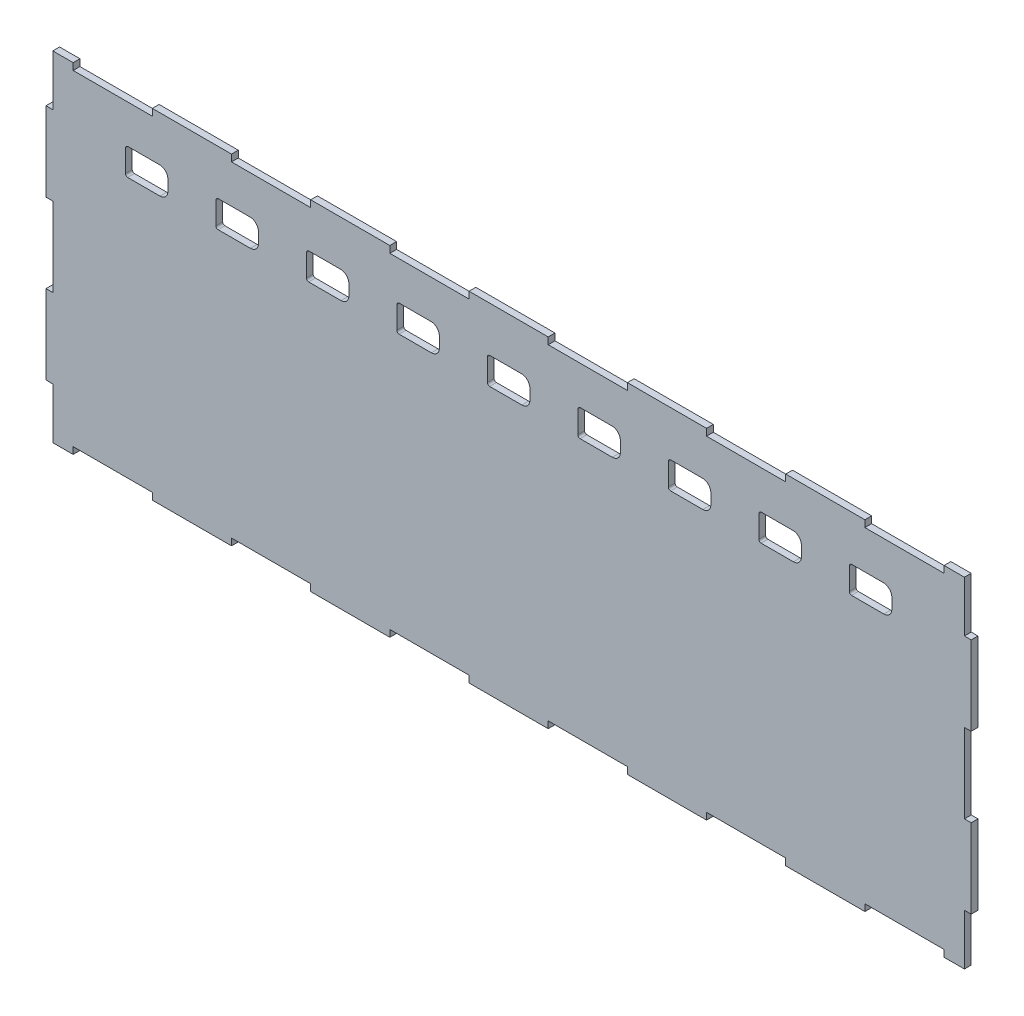
SolidWorks part; units mm, degrees
ref_plane "Front Plane" through (0, 0, 0) normal (0, 0, 1) x (1, 0, 0)
ref_plane "Top Plane" through (0, 0, 0) normal (0, 1, 0) x (1, 0, 0)
ref_plane "Right Plane" through (0, 0, 0) normal (1, 0, 0) x (0, 0, -1)
sketch "Model" plane through (0, 0, 0) normal (0, 0, 1) x (1, 0, 0)
  line L0 (201.5, 75) -> (192.5, 75)
  line L1 (192.5, 75) -> (192.5, 72)
  line L2 (192.5, 72) -> (157.5, 72)
  line L3 (157.5, 72) -> (157.5, 75)
  line L4 (157.5, 75) -> (122.5, 75)
  line L5 (122.5, 75) -> (122.5, 72)
  line L6 (122.5, 72) -> (87.5, 72)
  line L7 (87.5, 72) -> (87.5, 75)
  line L8 (87.5, 75) -> (52.5, 75)
  line L9 (52.5, 75) -> (52.5, 72)
  line L10 (52.5, 72) -> (17.5, 72)
  line L11 (17.5, 72) -> (17.5, 75)
  line L12 (17.5, 75) -> (-17.5, 75)
  line L13 (-17.5, 75) -> (-17.5, 72)
  line L14 (-17.5, 72) -> (-52.5, 72)
  line L15 (-52.5, 72) -> (-52.5, 75)
  line L16 (-52.5, 75) -> (-87.5, 75)
  line L17 (-87.5, 75) -> (-87.5, 72)
  line L18 (-87.5, 72) -> (-122.5, 72)
  line L19 (-122.5, 72) -> (-122.5, 75)
  line L20 (-122.5, 75) -> (-157.5, 75)
  line L21 (-157.5, 75) -> (-157.5, 72)
  line L22 (-157.5, 72) -> (-192.5, 72)
  line L23 (-192.5, 72) -> (-192.5, 75)
  line L24 (-192.5, 75) -> (-201.5, 75)
  line L25 (-201.5, 75) -> (-201.5, 72)
  line L26 (-201.5, 72) -> (-201.5, 52.5)
  line L27 (-201.5, 52.5) -> (-204.5, 52.5)
  line L28 (-204.5, 52.5) -> (-204.5, 17.5)
  line L29 (-204.5, 17.5) -> (-201.5, 17.5)
  line L30 (-201.5, 17.5) -> (-201.5, -17.5)
  line L31 (-201.5, -17.5) -> (-204.5, -17.5)
  line L32 (-204.5, -17.5) -> (-204.5, -52.5)
  line L33 (-204.5, -52.5) -> (-201.5, -52.5)
  line L34 (-201.5, -52.5) -> (-201.5, -72)
  line L35 (-201.5, -72) -> (-201.5, -75)
  line L36 (-201.5, -75) -> (-192.5, -75)
  line L37 (-192.5, -75) -> (-192.5, -72)
  line L38 (-192.5, -72) -> (-157.5, -72)
  line L39 (-157.5, -72) -> (-157.5, -75)
  line L40 (-157.5, -75) -> (-122.5, -75)
  line L41 (-122.5, -75) -> (-122.5, -72)
  line L42 (-122.5, -72) -> (-87.5, -72)
  line L43 (-87.5, -72) -> (-87.5, -75)
  line L44 (-87.5, -75) -> (-52.5, -75)
  line L45 (-52.5, -75) -> (-52.5, -72)
  line L46 (-52.5, -72) -> (-17.5, -72)
  line L47 (-17.5, -72) -> (-17.5, -75)
  line L48 (-17.5, -75) -> (17.5, -75)
  line L49 (17.5, -75) -> (17.5, -72)
  line L50 (17.5, -72) -> (52.5, -72)
  line L51 (52.5, -72) -> (52.5, -75)
  line L52 (52.5, -75) -> (87.5, -75)
  line L53 (87.5, -75) -> (87.5, -72)
  line L54 (87.5, -72) -> (122.5, -72)
  line L55 (122.5, -72) -> (122.5, -75)
  line L56 (122.5, -75) -> (157.5, -75)
  line L57 (157.5, -75) -> (157.5, -72)
  line L58 (157.5, -72) -> (192.5, -72)
  line L59 (192.5, -72) -> (192.5, -75)
  line L60 (192.5, -75) -> (201.5, -75)
  line L61 (201.5, -75) -> (201.5, -72)
  line L62 (201.5, -72) -> (201.5, -52.5)
  line L63 (201.5, -52.5) -> (204.5, -52.5)
  line L64 (204.5, -52.5) -> (204.5, -17.5)
  line L65 (204.5, -17.5) -> (201.5, -17.5)
  line L66 (201.5, -17.5) -> (201.5, 17.5)
  line L67 (201.5, 17.5) -> (204.5, 17.5)
  line L68 (204.5, 17.5) -> (204.5, 52.5)
  line L69 (204.5, 52.5) -> (201.5, 52.5)
  line L70 (201.5, 52.5) -> (201.5, 72)
  line L71 (201.5, 72) -> (201.5, 75)
extrude "Boss-Extrude1" add sketch "Model" along normal blind 3
sketch "Sketch1" plane through (0, 0, 3) normal (0, 0, 1) x (1, 0, 0)
  line L0 (-154.125, 43.1) -> (-168.4, 43.1)
  line L1 (-168.2, 55) -> (-154.325, 55)
  line L2 (-169.4, 44.1) -> (-169.4, 53.8)
  line L3 (-150.6, 46.625) -> (-150.6, 51.275)
  line L4 (-114.125, 43.1) -> (-128.4, 43.1)
  line L5 (-204.5, 48.95) -> (-169.4, 48.95) construction
  line L6 (-128.2, 55) -> (-114.325, 55)
  line L7 (-129.4, 44.1) -> (-129.4, 53.8)
  line L8 (-110.6, 46.625) -> (-110.6, 51.275)
  line L9 (-74.125, 43.1) -> (-88.4, 43.1)
  line L10 (-88.2, 55) -> (-74.325, 55)
  line L11 (-89.4, 44.1) -> (-89.4, 53.8)
  line L12 (-70.6, 46.625) -> (-70.6, 51.275)
  line L13 (-34.125, 43.1) -> (-48.4, 43.1)
  line L14 (-48.2, 55) -> (-34.325, 55)
  line L15 (-49.4, 44.1) -> (-49.4, 53.8)
  line L16 (-30.6, 46.625) -> (-30.6, 51.275)
  line L17 (5.875, 43.1) -> (-8.4, 43.1)
  line L18 (-8.2, 55) -> (5.675, 55)
  line L19 (-9.4, 44.1) -> (-9.4, 53.8)
  line L20 (9.4, 46.625) -> (9.4, 51.275)
  line L21 (45.875, 43.1) -> (31.6, 43.1)
  line L22 (31.8, 55) -> (45.675, 55)
  line L23 (30.6, 44.1) -> (30.6, 53.8)
  line L24 (49.4, 46.625) -> (49.4, 51.275)
  line L25 (85.875, 43.1) -> (71.6, 43.1)
  line L26 (71.8, 55) -> (85.675, 55)
  line L27 (70.6, 44.1) -> (70.6, 53.8)
  line L28 (89.4, 46.625) -> (89.4, 51.275)
  line L29 (125.875, 43.1) -> (111.6, 43.1)
  line L30 (111.8, 55) -> (125.675, 55)
  line L31 (110.6, 44.1) -> (110.6, 53.8)
  line L32 (129.4, 46.625) -> (129.4, 51.275)
  line L33 (165.875, 43.1) -> (151.6, 43.1)
  line L34 (151.8, 55) -> (165.675, 55)
  line L35 (150.6, 44.1) -> (150.6, 53.8)
  line L36 (169.4, 46.625) -> (169.4, 51.275)
  line L37 (-161.2625, 55) -> (-161.2625, 75) construction
  line L39 (169.4, 48.95) -> (204.5, 48.95) construction
  line L41 (-204.5, 52.5) -> (-204.5, 17.5) construction
  line L42 (204.5, 17.5) -> (204.5, 52.5) construction
  arc A0 (-150.6, 46.625) -> (-154.125, 43.1) centre (-154.125, 46.625) cw
  arc A1 (-150.6, 51.275) -> (-154.325, 55) centre (-154.325, 51.275) ccw
  arc A2 (-168.4, 43.1) -> (-169.4, 44.1) centre (-168.4, 44.1) cw
  arc A3 (-169.4, 53.8) -> (-168.2, 55) centre (-168.2, 53.8) cw
  arc A4 (-110.6, 46.625) -> (-114.125, 43.1) centre (-114.125, 46.625) cw
  arc A5 (-110.6, 51.275) -> (-114.325, 55) centre (-114.325, 51.275) ccw
  arc A6 (-128.4, 43.1) -> (-129.4, 44.1) centre (-128.4, 44.1) cw
  arc A7 (-129.4, 53.8) -> (-128.2, 55) centre (-128.2, 53.8) cw
  arc A8 (-70.6, 46.625) -> (-74.125, 43.1) centre (-74.125, 46.625) cw
  arc A9 (-70.6, 51.275) -> (-74.325, 55) centre (-74.325, 51.275) ccw
  arc A10 (-88.4, 43.1) -> (-89.4, 44.1) centre (-88.4, 44.1) cw
  arc A11 (-89.4, 53.8) -> (-88.2, 55) centre (-88.2, 53.8) cw
  arc A12 (-30.6, 46.625) -> (-34.125, 43.1) centre (-34.125, 46.625) cw
  arc A13 (-30.6, 51.275) -> (-34.325, 55) centre (-34.325, 51.275) ccw
  arc A14 (-48.4, 43.1) -> (-49.4, 44.1) centre (-48.4, 44.1) cw
  arc A15 (-49.4, 53.8) -> (-48.2, 55) centre (-48.2, 53.8) cw
  arc A16 (9.4, 46.625) -> (5.875, 43.1) centre (5.875, 46.625) cw
  arc A17 (9.4, 51.275) -> (5.675, 55) centre (5.675, 51.275) ccw
  arc A18 (-8.4, 43.1) -> (-9.4, 44.1) centre (-8.4, 44.1) cw
  arc A19 (-9.4, 53.8) -> (-8.2, 55) centre (-8.2, 53.8) cw
  arc A20 (49.4, 46.625) -> (45.875, 43.1) centre (45.875, 46.625) cw
  arc A21 (49.4, 51.275) -> (45.675, 55) centre (45.675, 51.275) ccw
  arc A22 (31.6, 43.1) -> (30.6, 44.1) centre (31.6, 44.1) cw
  arc A23 (30.6, 53.8) -> (31.8, 55) centre (31.8, 53.8) cw
  arc A24 (89.4, 46.625) -> (85.875, 43.1) centre (85.875, 46.625) cw
  arc A25 (89.4, 51.275) -> (85.675, 55) centre (85.675, 51.275) ccw
  arc A26 (71.6, 43.1) -> (70.6, 44.1) centre (71.6, 44.1) cw
  arc A27 (70.6, 53.8) -> (71.8, 55) centre (71.8, 53.8) cw
  arc A28 (129.4, 46.625) -> (125.875, 43.1) centre (125.875, 46.625) cw
  arc A29 (129.4, 51.275) -> (125.675, 55) centre (125.675, 51.275) ccw
  arc A30 (111.6, 43.1) -> (110.6, 44.1) centre (111.6, 44.1) cw
  arc A31 (110.6, 53.8) -> (111.8, 55) centre (111.8, 53.8) cw
  arc A32 (169.4, 46.625) -> (165.875, 43.1) centre (165.875, 46.625) cw
  arc A33 (169.4, 51.275) -> (165.675, 55) centre (165.675, 51.275) ccw
  arc A34 (151.6, 43.1) -> (150.6, 44.1) centre (151.6, 44.1) cw
  arc A35 (150.6, 53.8) -> (151.8, 55) centre (151.8, 53.8) cw
  dimension "D1" = 20
  dimension "D2" = 35.1
extrude "Cut-Extrude1" cut sketch "Sketch1" against normal through all
